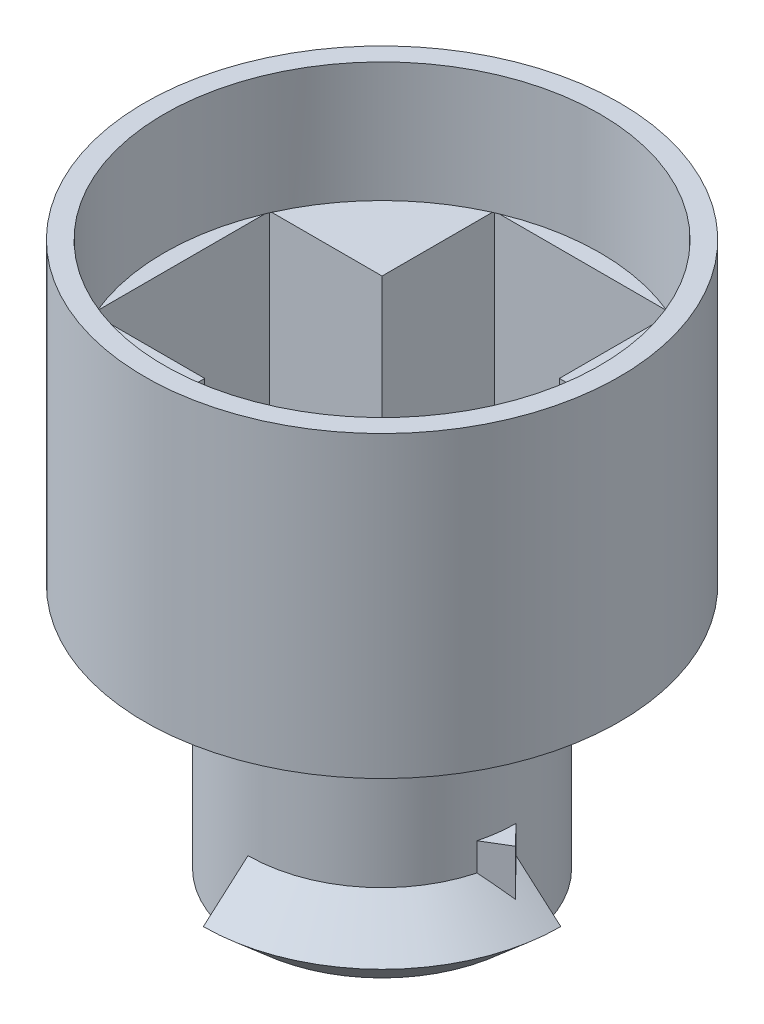
SolidWorks part; units mm, degrees
ref_plane "Front Plane" through (0, 0, 0) normal (0, 0, 1) x (1, 0, 0)
ref_plane "Top Plane" through (0, 0, 0) normal (0, 1, 0) x (1, 0, 0)
ref_plane "Right Plane" through (0, 0, 0) normal (1, 0, 0) x (0, 0, -1)
sketch "Sketch1" plane through (0, 0, 0) normal (0, 0, 1) x (1, 0, 0)
  line L0 (0, 0) -> (4.8, 0)
  line L1 (4.8, 0) -> (4.8, 7)
  line L2 (4.8, 7) -> (8.5, 8.8)
  line L3 (8.5, 8.8) -> (8.5, 19.5)
  line L5 (4.25, 15.2) -> (4.25, 9)
  line L6 (4.25, 9) -> (4, 9)
  line L7 (4, 9) -> (4, 1.5)
  line L8 (4, 1.5) -> (0, 1.5)
  line L9 (0, 1.5) -> (0, 0)
  line L10 (0, 0) -> (0, 53.0452) construction
  line L11 (4.25, 15.2) -> (7.8, 15.2)
  line L12 (7.8, 15.2) -> (7.8, 19.5)
  line L13 (7.8, 19.5) -> (8.5, 19.5)
  line L14 (4.25, 9) -> (9.4433, 9) construction
  line L15 (4.8, 7) -> (4.8, 8.6136) construction
  dimension "D1" = 9.6
  dimension "D2" = 1.5
  dimension "D3" = 8
  dimension "D4" = 0.8
  dimension "D5" = 64.058
  dimension "D6" = 17
  dimension "D7" = 8.5
  dimension "D8" = 0.2
  dimension "D9" = 19.5
  dimension "15.6" = 15.6
  dimension "D10" = 4.3
  dimension "D11" = 6.2
  dimension "D13" = 9
  dimension "D14" = 2
revolve "Revolve1" add sketch "Sketch1" angle 360 about L10
sketch "Sketch2" plane through (0, 15.2, 0) normal (0, 1, 0) x (1, 0, 0)
  line L1 (-3.175, -7.2) -> (3.175, -7.2)
  line L2 (-3.175, -7.2) -> (-3.175, 7.2)
  line L3 (-3.175, 7.2) -> (3.175, 7.2)
  line L4 (3.175, -7.2) -> (3.175, 7.2)
  line L5 (-3.175, -7.2) -> (3.175, 7.2) construction
  line L6 (-3.175, 7.2) -> (3.175, -7.2) construction
  point P0 (0, 0)
  dimension "D1" = 14.4
  dimension "D2" = 6.35
extrude "Cut-Extrude1" cut sketch "Sketch2" against normal up to surface (6.2 mm away) up to face at (0, 9, -4)
pattern_circular "CirPattern1" count 4 over 360 about axis through (0, 0, 0) along (0, 1, 0) of "Cut-Extrude1"
sketch "Sketch3" plane through (0, 1.5, 0) normal (0, 1, 0) x (1, 0, 0)
  line L1 (-1.6, -1.6) -> (1.6, -1.6)
  line L2 (-1.6, -1.6) -> (-1.6, 1.6)
  line L3 (-1.6, 1.6) -> (1.6, 1.6)
  line L4 (1.6, -1.6) -> (1.6, 1.6)
  line L5 (-1.6, -1.6) -> (1.6, 1.6) construction
  line L6 (-1.6, 1.6) -> (1.6, -1.6) construction
  point P0 (0, 0)
  dimension "D1" = 3.2
  dimension "D2" = 3.2
extrude "Cut-Extrude2" cut sketch "Sketch3" against normal through all
sketch "Sketch4" plane through (0, 9, 0) normal (0, 1, 0) x (1, 0, 0)
  line L0 (0, 0) -> (0, 7.3619) construction
  line L1 (-3.075, 7.2) -> (-1.275, 7.2)
  line L2 (-3.075, 7.2) -> (-3.075, 5.4)
  line L3 (-3.075, 5.4) -> (-1.275, 5.4)
  line L4 (-1.275, 7.2) -> (-1.275, 5.4)
  line L5 (1.275, 7.2) -> (1.275, 5.4)
  line L6 (3.075, 5.4) -> (1.275, 5.4)
  line L7 (3.075, 7.2) -> (3.075, 5.4)
  line L8 (3.075, 7.2) -> (1.275, 7.2)
  line L9 (-3.175, 7.2) -> (3.175, 7.2) construction
  line L10 (-3.175, 3.175) -> (-3.175, 7.2) construction
  dimension "D1" = 1.8
  dimension "D2" = 1.8
  dimension "D3" = 0.1
extrude "Cut-Extrude3" cut sketch "Sketch4" against normal through all
fillet "Fillet1" radius 0.5 2 edges at (3.075, 8.7368, -7.2) (-3.075, 8.7368, -7.2)
pattern_circular "CirPattern2" count 4 over 360 about axis through (0, 0, 0) along (0, 1, 0) of "Cut-Extrude3", "Fillet1"
sketch "Sketch5" plane through (0, 15.2, 0) normal (0, 1, 0) x (1, 0, 0)
  line L3 (4.773, 4.773) -> (-4.773, -4.773) construction
  line L4 (0, 0) -> (0.9105, 0) construction
  circle A0 centre (4.773, 4.773) radius 0.95
  circle A1 centre (-4.773, -4.773) radius 0.95
  point P2 (0, 0)
  dimension "D1" = 1.9
  dimension "D2" = 45
  dimension "D4" = 13.5
extrude "Cut-Extrude4" cut sketch "Sketch5" against normal blind 6
sketch "Sketch6" plane through (0, 0, 0) normal (1, 0, 0) x (0, 0, -1)
  line L0 (-4.8, 2.8) -> (-6.4, 1.4)
  line L1 (-4.8, 7) -> (-4.8, 0) construction
  line L2 (-6.4, 1.4) -> (-4.8, 0)
  line L3 (-4.8, 2.8) -> (-4.8, 0)
  line L4 (0, 0) -> (0, 3.7118) construction
  line L5 (4.8, 2.8) -> (4.8, 0)
  line L6 (6.4, 1.4) -> (4.8, 0)
  line L7 (4.8, 2.8) -> (6.4, 1.4)
  dimension "D1" = 1.6
  dimension "D2" = 2.8
revolve "Revolve2" add sketch "Sketch6" angle 90 about L4
ref_plane "Plane1" through (0, 2.8, 0) normal (0, 1, 0) x (1, 0, 0)
sketch "Sketch7" plane through (0, 2.8, 0) normal (0, 1, 0) x (1, 0, 0)
  line L0 (4.8, 0) -> (5.4926, -0.7213)
  line L1 (5.4926, -0.7213) -> (4.6372, -1.2394)
  line L2 (4.6372, -1.2394) -> (4.8, 0)
  line L3 (0, 0) -> (0.3506, 2.67) construction
  line L4 (-4.8, 0) -> (-4.6372, 1.2394)
  line L5 (-5.4926, 0.7213) -> (-4.8, 0)
  line L6 (-4.6372, 1.2394) -> (-5.4926, 0.7213)
  arc A0 (0, -4.8) -> (4.8, 0) centre (0, 0) ccw construction
  dimension "D1" = 1
  dimension "D2" = 1.25
extrude "Boss-Extrude1" add sketch "Sketch7" along normal blind 1 and the other way up to next
sketch "Sketch8" plane through (0, 0, 0) normal (0, -1, 0) x (1, 0, 0)
  circle A0 centre (0, 0) radius 2.2627
  dimension "D1" = 4.5255
extrude "Cut-Extrude5" cut sketch "Sketch8" against normal blind 0.6
